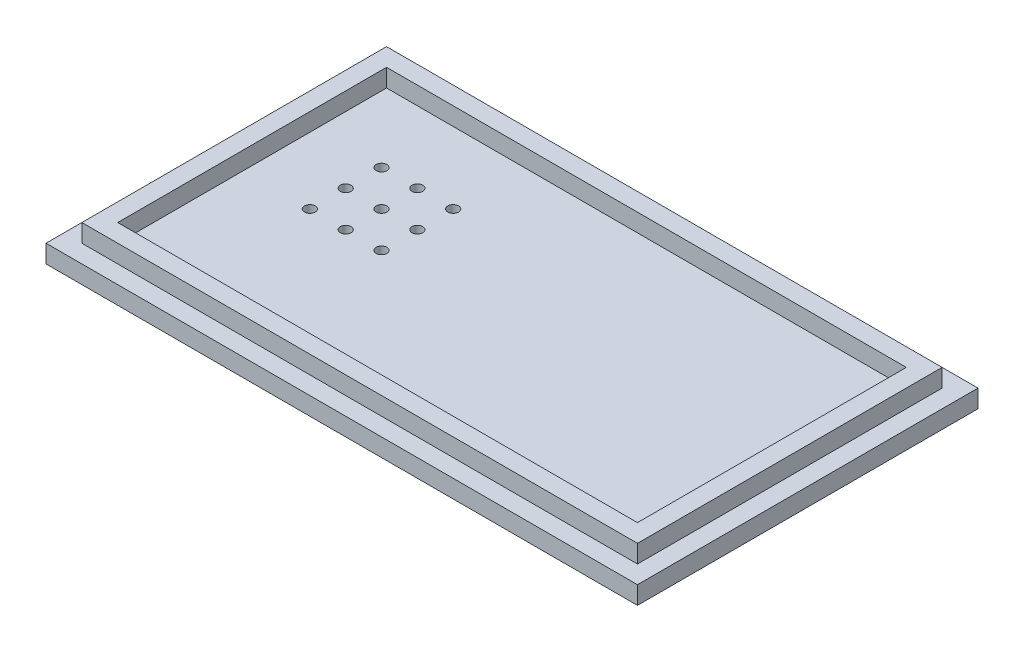
SolidWorks part; units mm, degrees
ref_plane "Front Plane" through (0, 0, 0) normal (0, 0, 1) x (1, 0, 0)
ref_plane "Top Plane" through (0, 0, 0) normal (0, 1, 0) x (1, 0, 0)
ref_plane "Right Plane" through (0, 0, 0) normal (1, 0, 0) x (0, 0, -1)
sketch "Sketch1" plane through (0, 0, 0) normal (0, 1, 0) x (1, 0, 0)
  line L1 (-82.5, 47.5) -> (82.5, 47.5)
  line L2 (-82.5, 47.5) -> (-82.5, -47.5)
  line L3 (-82.5, -47.5) -> (82.5, -47.5)
  line L4 (82.5, 47.5) -> (82.5, -47.5)
  line L5 (-82.5, 47.5) -> (82.5, -47.5) construction
  line L6 (-82.5, -47.5) -> (82.5, 47.5) construction
  point P0 (0, 0)
  dimension "D1" = 165
  dimension "D2" = 95
extrude "Boss-Extrude1" add sketch "Sketch1" along normal blind 5
sketch "Sketch2" plane through (0, 5, 0) normal (0, 1, 0) x (1, 0, 0)
  line L1 (-77.5, 42.5) -> (77.5, 42.5)
  line L2 (-77.5, 42.5) -> (-77.5, -42.5)
  line L3 (-77.5, -42.5) -> (77.5, -42.5)
  line L4 (77.5, 42.5) -> (77.5, -42.5)
  line L5 (-77.5, 42.5) -> (77.5, -42.5) construction
  line L6 (-77.5, -42.5) -> (77.5, 42.5) construction
  line L7 (-72.5, 37.5) -> (72.5, 37.5)
  line L8 (-72.5, 37.5) -> (-72.5, -37.5)
  line L9 (-72.5, -37.5) -> (72.5, -37.5)
  line L10 (72.5, 37.5) -> (72.5, -37.5)
  line L11 (-72.5, 37.5) -> (72.5, -37.5) construction
  line L12 (-72.5, -37.5) -> (72.5, 37.5) construction
  point P0 (0, 0)
  point P6 (0, 0)
  dimension "D1" = 85
  dimension "D2" = 155
  dimension "D3" = 145
  dimension "D4" = 75
extrude "Boss-Extrude2" add sketch "Sketch2" along normal blind 5
sketch "Sketch3" plane through (0, 5, 0) normal (0, 1, 0) x (1, 0, 0)
  circle A0 centre (-53.9734, 17.5727) radius 1.5
  circle A1 centre (-43.9734, 17.5727) radius 1.5
  circle A2 centre (-33.9734, 17.5727) radius 1.5
  circle A3 centre (-43.9734, 7.5727) radius 1.5
  circle A4 centre (-33.9734, 7.5727) radius 1.5
  circle A5 centre (-43.9734, -2.4273) radius 1.5
  circle A6 centre (-33.9734, -2.4273) radius 1.5
  circle A7 centre (-53.9734, 7.5727) radius 1.5
  circle A8 centre (-53.9734, -2.4273) radius 1.5
  dimension "D1" = 3
  dimension "D2" = 3
  dimension "D3" = 3
extrude "Cut-Extrude1" cut sketch "Sketch3" against normal up to surface (5 mm away) up to face at (0, 0, 0)
